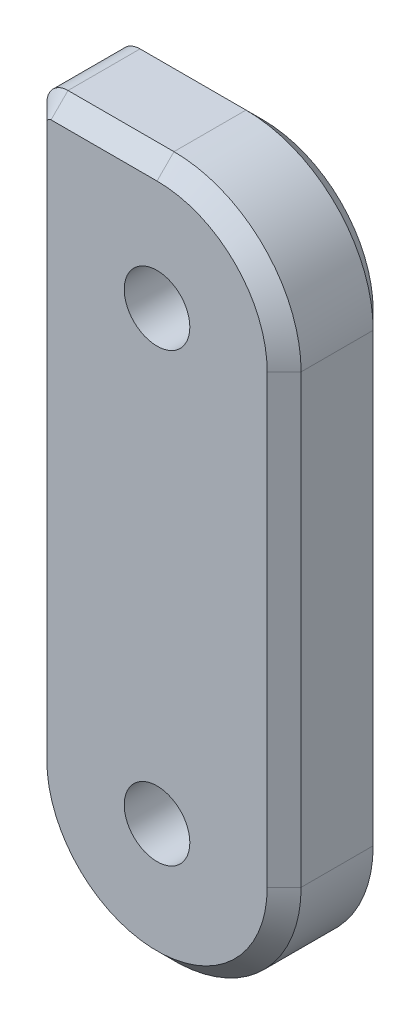
SolidWorks part; units mm, degrees
material "PET"
ref_plane "Front Plane" through (0, 0, 0) normal (0, 0, 1) x (1, 0, 0)
ref_plane "Top Plane" through (0, 0, 0) normal (0, 1, 0) x (1, 0, 0)
ref_plane "Right Plane" through (0, 0, 0) normal (1, 0, 0) x (0, 0, -1)
sketch "Sketch2" plane through (0, 0, 0) normal (0, 0, 1) x (1, 0, 0)
  line L0 (0, -218.6158) -> (0, -202.8355) construction
  line L1 (-9.525, 42.9692) -> (-9.525, 0)
  line L2 (9.525, 33.4442) -> (9.525, 0)
  line L4 (-9.525, 42.9692) -> (0, 42.9692)
  arc A0 (-9.525, 0) -> (9.525, 0) centre (0, 0) ccw
  arc A1 (9.525, 33.4442) -> (0, 42.9692) centre (0, 33.4442) ccw
  dimension "D1" = 19.05
  dimension "D3" = 19.05
  dimension "D2" = 33.4442
extrude "Boss-Extrude1" add sketch "Sketch2" along normal blind 7.9375
hole_wizard "#8 Clearance Hole1" positions "Sketch3" profile "Sketch4" hole size "#8" standard "ANSI Inch" end condition up to next
sketch "Sketch3" plane through (0, 0, 7.9375) normal (0, 0, 1) x (1, 0, 0)
  point P0 (0, 0)
sketch "Sketch4" plane through (0, 0, 7.9375) normal (1, 0, 0) x (0, -1, 0)
  line L0 (0, 0) -> (0, 7.9375)
  line L1 (0, 7.9375) -> (2.4574, 7.9375)
  line L2 (2.4574, 7.9375) -> (2.4574, 0)
  line L5 (2.4574, 0) -> (0, 0)
  line L11 (0, -6.35) -> (0, 107.95) construction
  dimension "Thru Hole Dia." = 4.9149
  dimension "Thru Hole Depth" = 7.9375
hole_wizard "#8 Clearance Hole2" positions "Sketch5" profile "Sketch6" hole size "#8" standard "ANSI Inch" end condition up to next
sketch "Sketch5" plane through (0, 0, 7.9375) normal (0, 0, 1) x (1, 0, 0)
  point P0 (0, 33.4442)
sketch "Sketch6" plane through (0, 33.4442, 7.9375) normal (1, 0, 0) x (0, -1, 0)
  line L0 (0, 0) -> (0, 7.9375)
  line L1 (0, 7.9375) -> (2.4574, 7.9375)
  line L2 (2.4574, 7.9375) -> (2.4574, 0)
  line L5 (2.4574, 0) -> (0, 0)
  line L11 (0, -6.35) -> (0, 107.95) construction
  dimension "Thru Hole Dia." = 4.9149
  dimension "Thru Hole Depth" = 7.9375
sketch "Sketch7" plane through (0, 0, 0) normal (0, 0, -1) x (-1, 0, 0)
  circle A0 centre (0, 33.4442) radius 9.525 construction
  circle A1 centre (0, 33.4442) radius 5.08
  dimension "D1" = 19.05
  dimension "D2" = 10.16
extrude "Cut-Extrude1" cut sketch "Sketch7" against normal blind 2.032
fillet "Fillet1" radius 1.5875 1 edges at (-9.525, 42.9692, 3.9688)
chamfer "Chamfer2" distance 1.27 angle 45 12 edges at (6.7352, 40.1794, 0) (-3.9688, 42.9692, 0) (9.525, 16.7221, 0) (-9.06, 42.5042, 0) (0, -9.525, 0) (-9.525, 20.6908, 0) (6.7352, 40.1794, 7.9375) (-3.9688, 42.9692, 7.9375) (9.525, 16.7221, 7.9375) (-9.06, 42.5042, 7.9375) (0, -9.525, 7.9375) (-9.525, 20.6908, 7.9375)
